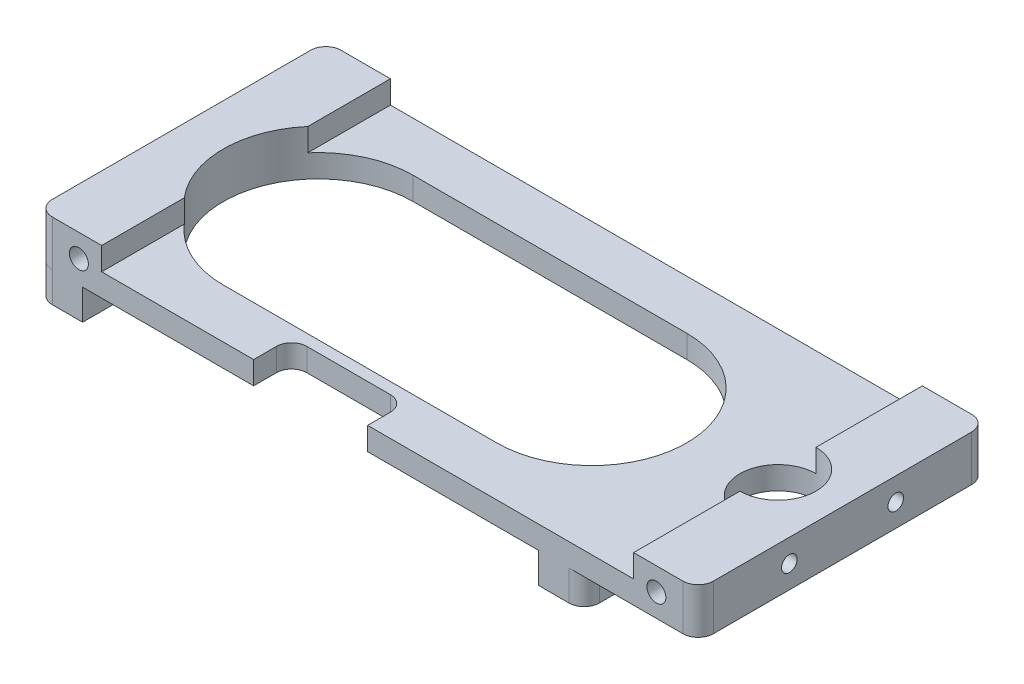
SolidWorks part; units mm, degrees
ref_plane "Front Plane" through (0, 0, 0) normal (0, 0, 1) x (1, 0, 0)
ref_plane "Top Plane" through (0, 0, 0) normal (0, 1, 0) x (1, 0, 0)
ref_plane "Right Plane" through (0, 0, 0) normal (1, 0, 0) x (0, 0, -1)
sketch "Sketch2" plane through (0, 0, 11) normal (0, 0, 1) x (1, 0, 0)
  line L1 (-84.0653, 85.9519) -> (-75.5653, 85.9519)
  line L2 (-84.0653, 85.9519) -> (-84.0653, 79.9519)
  line L3 (-84.0653, 79.9519) -> (2.9347, 79.9519)
  line L4 (2.9347, 85.9519) -> (2.9347, 79.9519)
  line L5 (-71.5653, 86.4519) -> (-82.0653, 86.4519) construction
  line L14 (-5.5653, 85.9519) -> (2.9347, 85.9519)
  line L16 (-75.5653, 85.9519) -> (-75.5653, 82.9519)
  line L17 (-75.5653, 82.9519) -> (-5.5653, 82.9519)
  line L18 (-5.5653, 85.9519) -> (-5.5653, 82.9519)
  circle A0 centre (-2.5653, 82.9519) radius 3 construction
  dimension "D1" = 0.5
  dimension "D2" = 5.5
  dimension "D3" = 5.5
  dimension "D4" = 6
  dimension "D5" = 3
  dimension "D6" = 8.5
extrude "Boss-Extrude1" add sketch "Sketch2" along normal blind 38
fillet "Fillet3" radius 2 4 edges at (-84.0653, 82.9519, 49) (-84.0653, 82.9519, 11) (2.9347, 82.9519, 11) (2.9347, 82.9519, 49)
sketch "Sketch3" plane through (0, 82.9519, 0) normal (0, 1, 0) x (1, 0, 0)
  line L0 (-84.0653, -47) -> (-84.0653, -13) construction
  line L1 (-5.5653, -11) -> (-75.5653, -11) construction
  line L2 (-66.0653, -42.5) -> (-30.0653, -42.5)
  line L3 (-66.0653, -17.5) -> (-30.0653, -17.5)
  line L4 (-40.5653, -49) -> (-40.5653, -44)
  line L5 (-5.5653, -49) -> (-75.5653, -49) construction
  line L6 (-40.5653, -44) -> (-55.5653, -44)
  line L7 (-55.5653, -44) -> (-55.5653, -49)
  line L8 (-40.5653, -49) -> (-55.5653, -49)
  line L9 (-75.5653, -49) -> (-75.5653, -11) construction
  arc A0 (-30.0653, -42.5) -> (-30.0653, -17.5) centre (-30.0653, -30) ccw
  arc A1 (-66.0653, -17.5) -> (-66.0653, -42.5) centre (-66.0653, -30) ccw
  dimension "D1" = 25
  dimension "D2" = 18
  dimension "D5" = 5
  dimension "D6" = 20
  dimension "D7" = 15
  dimension "D3" = 36
  dimension "D4" = 19
extrude "Cut-Extrude1" cut sketch "Sketch3" against normal through all and the other way through all
hole_wizard "M3x0.5 Tapped Hole3" positions "Sketch7" profile "Sketch6" tap size "M3x0.5" standard "Ansi Metric"
sketch "Sketch7" plane through (0, 0, 49) normal (0, 0, 1) x (1, 0, 0)
  line L0 (-75.5653, 82.9519) -> (-75.5653, 85.9519) construction
  line L1 (-82.0653, 79.9519) -> (-55.5653, 79.9519) construction
  line L2 (-5.5653, 85.9519) -> (-5.5653, 82.9519) construction
  point P0 (-78.5653, 82.9519)
  point P1 (-2.5653, 82.9519)
  dimension "D1" = 3
  dimension "D2" = 3
  dimension "D3" = 3
  dimension "D4" = 3
sketch "Sketch6" plane through (-78.5653, 82.9519, 49) normal (1, 0, 0) x (0, -1, 0)
  line L0 (0, 0) -> (0, 8.2511)
  line L1 (0, 8.2511) -> (1.25, 7.5)
  line L2 (1.25, 7.5) -> (1.25, 0)
  line L5 (1.25, 0) -> (0, 0)
  line L10 (0, 8.2511) -> (-1.25, 7.5) construction
  line L11 (0, -6.35) -> (0, 107.95) construction
  dimension "Tap Drill Dia." = 2.5
  dimension "Tap Drill Depth" = 7.5
  dimension "Drill Angle" = 118
cosmetic thread "Hole Thread6" parameters "D1"=6, "D2"=3
cosmetic thread "Hole Thread7" parameters "D1"=6, "D2"=3
hole_wizard "M3x0.5 Tapped Hole4" positions "Sketch9" profile "Sketch8" tap size "M3x0.5" standard "Ansi Metric"
sketch "Sketch9" plane through (0, 0, 11) normal (0, 0, -1) x (-1, 0, 0)
  line L0 (75.5653, 82.9519) -> (75.5653, 85.9519) construction
  line L1 (82.0653, 79.9519) -> (-0.9347, 79.9519) construction
  line L2 (-0.9347, 85.9519) -> (5.5653, 85.9519) construction
  line L3 (5.5653, 85.9519) -> (5.5653, 82.9519) construction
  point P0 (2.5653, 82.9519)
  point P1 (78.5653, 82.9519)
  dimension "D1" = 3
  dimension "D2" = 3
  dimension "D3" = 3
  dimension "D4" = 3
sketch "Sketch8" plane through (-2.5653, 82.9519, 11) normal (1, 0, 0) x (0, 1, 0)
  line L0 (0, 0) -> (0, 8.2511)
  line L1 (0, 8.2511) -> (1.25, 7.5)
  line L2 (1.25, 7.5) -> (1.25, 0)
  line L5 (1.25, 0) -> (0, 0)
  line L10 (0, 8.2511) -> (-1.25, 7.5) construction
  line L11 (0, -6.35) -> (0, 107.95) construction
  dimension "Tap Drill Dia." = 2.5
  dimension "Tap Drill Depth" = 7.5
  dimension "Drill Angle" = 118
cosmetic thread "Hole Thread8" parameters "D1"=6, "D2"=3
cosmetic thread "Hole Thread9" parameters "D1"=6, "D2"=3
hole_wizard "M2.5x0.45 Tapped Hole1" positions "Sketch11" profile "Sketch10" tap size "M2.5x0.45" standard "Ansi Metric"
sketch "Sketch11" plane through (-84.0653, 0, 0) normal (-1, 0, 0) x (0, 0, 1)
  line L0 (11, 79.9519) -> (11, 85.9519) construction
  line L1 (47, 79.9519) -> (13, 79.9519) construction
  point P0 (23, 82.9519)
  point P1 (37, 82.9519)
  dimension "D1" = 12
  dimension "D2" = 3
  dimension "D3" = 3
  dimension "D4" = 12
sketch "Sketch10" plane through (-84.0653, 82.9519, 23) normal (0, 1, 0) x (0, 0, 1)
  line L0 (0, 0) -> (0, 6.9659)
  line L1 (0, 6.9659) -> (1.025, 6.35)
  line L2 (1.025, 6.35) -> (1.025, 0)
  line L5 (1.025, 0) -> (0, 0)
  line L10 (0, 6.9659) -> (-1.025, 6.35) construction
  line L11 (0, -6.35) -> (0, 107.95) construction
  dimension "Tap Drill Dia." = 2.05
  dimension "Tap Drill Depth" = 6.35
  dimension "Drill Angle" = 118
cosmetic thread "Hole Thread10" parameters "D1"=5, "D2"=2.5
cosmetic thread "Hole Thread11" parameters "D1"=5, "D2"=2.5
hole_wizard "M2.5x0.45 Tapped Hole2" positions "Sketch13" profile "Sketch12" tap size "M2.5x0.45" standard "Ansi Metric"
sketch "Sketch13" plane through (2.9347, 0, 0) normal (1, 0, 0) x (0, 0, -1)
  line L0 (-49, 79.9519) -> (-49, 85.9519) construction
  line L1 (-47, 79.9519) -> (-13, 79.9519) construction
  line L2 (-11, 85.9519) -> (-11, 79.9519) construction
  point P0 (-37, 82.9519)
  point P1 (-23, 82.9519)
  dimension "D1" = 12
  dimension "D2" = 3
  dimension "D3" = 3
  dimension "D4" = 12
sketch "Sketch12" plane through (2.9347, 82.9519, 37) normal (0, 1, 0) x (0, 0, -1)
  line L0 (0, 0) -> (0, 6.9659)
  line L1 (0, 6.9659) -> (1.025, 6.35)
  line L2 (1.025, 6.35) -> (1.025, 0)
  line L5 (1.025, 0) -> (0, 0)
  line L10 (0, 6.9659) -> (-1.025, 6.35) construction
  line L11 (0, -6.35) -> (0, 107.95) construction
  dimension "Tap Drill Dia." = 2.05
  dimension "Tap Drill Depth" = 6.35
  dimension "Drill Angle" = 118
cosmetic thread "Hole Thread12" parameters "D1"=5, "D2"=2.5
cosmetic thread "Hole Thread13" parameters "D1"=5, "D2"=2.5
sketch "Sketch14" plane through (0, 85.9519, 0) normal (0, 1, 0) x (1, 0, 0)
  line L0 (-5.5653, -49) -> (-5.5653, -11) construction
  circle A0 centre (-5.5653, -30) radius 5
  dimension "D1" = 10
extrude "Cut-Extrude2" cut sketch "Sketch14" against normal through all
sketch "Sketch16" plane through (0, 79.9519, 0) normal (0, -1, 0) x (1, 0, 0)
  line L0 (-82.0653, 49) -> (-55.5653, 49) construction
  line L1 (-84.0653, 49) -> (-78.0653, 49)
  line L2 (-84.0653, 49) -> (-84.0653, 43)
  line L3 (-84.0653, 43) -> (-78.0653, 43)
  line L4 (-78.0653, 49) -> (-78.0653, 43)
  line L5 (-84.0653, 11) -> (-78.0653, 11)
  line L6 (-84.0653, 11) -> (-84.0653, 17)
  line L7 (-84.0653, 17) -> (-78.0653, 17)
  line L8 (-78.0653, 11) -> (-78.0653, 17)
  line L9 (-12.0653, 49) -> (-18.0653, 49)
  line L10 (-12.0653, 49) -> (-12.0653, 43)
  line L11 (-12.0653, 43) -> (-18.0653, 43)
  line L12 (-18.0653, 49) -> (-18.0653, 43)
  line L13 (-82.0653, 11) -> (0.9347, 11) construction
  line L14 (-12.0653, 11) -> (-18.0653, 11)
  line L15 (-12.0653, 11) -> (-12.0653, 17)
  line L16 (-12.0653, 17) -> (-18.0653, 17)
  line L17 (-18.0653, 11) -> (-18.0653, 17)
  line L18 (-84.0653, 47) -> (-84.0653, 13) construction
  dimension "D1" = 6
  dimension "D2" = 6
  dimension "D3" = 6
  dimension "D4" = 6
  dimension "D5" = 6
  dimension "D6" = 6
  dimension "D7" = 6
  dimension "D8" = 6
  dimension "D9" = 60
  dimension "D10" = 60
extrude "Boss-Extrude2" add sketch "Sketch16" along normal blind 4
fillet "Fillet4" radius 2 10 edges at (-12.0653, 77.9519, 11) (-84.0653, 77.9519, 11) (-84.0653, 77.9519, 49) (-78.0653, 77.9519, 43) (-78.0653, 77.9519, 17) (-18.0653, 77.9519, 17) (-18.0653, 77.9519, 43) (-12.0653, 77.9519, 49) (-40.5653, 81.4519, 44) (-55.5653, 81.4519, 44)
hole_wizard "M3x0.5 Tapped Hole5" positions "Sketch18" profile "Sketch17" tap size "M3x0.5" standard "Ansi Metric"
sketch "Sketch18" plane through (0, 75.9519, 0) normal (0, -1, 0) x (1, 0, 0)
  line L0 (-16.0653, 43) -> (-12.0653, 43) construction
  line L1 (-18.0653, 49) -> (-18.0653, 45) construction
  line L2 (-12.0653, 17) -> (-16.0653, 17) construction
  line L3 (-18.0653, 15) -> (-18.0653, 11) construction
  line L5 (-80.0653, 17) -> (-84.0653, 17) construction
  line L6 (-78.0653, 11) -> (-78.0653, 15) construction
  line L7 (-84.0653, 43) -> (-80.0653, 43) construction
  line L8 (-78.0653, 45) -> (-78.0653, 49) construction
  point P0 (-81.0653, 46)
  point P1 (-81.0653, 14)
  point P3 (-15.0653, 14)
  point P5 (-15.0653, 46)
  dimension "D1" = 3
  dimension "D2" = 3
  dimension "D3" = 3
  dimension "D4" = 3
  dimension "D5" = 3
  dimension "D6" = 3
  dimension "D7" = 3
  dimension "D8" = 3
sketch "Sketch17" plane through (-81.0653, 75.9519, 46) normal (1, 0, 0) x (0, 0, -1)
  line L0 (0, 0) -> (0, 6.2511)
  line L1 (0, 6.2511) -> (1.25, 5.5)
  line L2 (1.25, 5.5) -> (1.25, 0)
  line L5 (1.25, 0) -> (0, 0)
  line L10 (0, 6.2511) -> (-1.25, 5.5) construction
  line L11 (0, -6.35) -> (0, 107.95) construction
  dimension "Tap Drill Dia." = 2.5
  dimension "Tap Drill Depth" = 5.5
  dimension "Drill Angle" = 118
cosmetic thread "Hole Thread14" parameters "D1"=5, "D2"=3
cosmetic thread "Hole Thread15" parameters "D1"=5, "D2"=3
cosmetic thread "Hole Thread16" parameters "D1"=5, "D2"=3
cosmetic thread "Hole Thread17" parameters "D1"=5, "D2"=3
